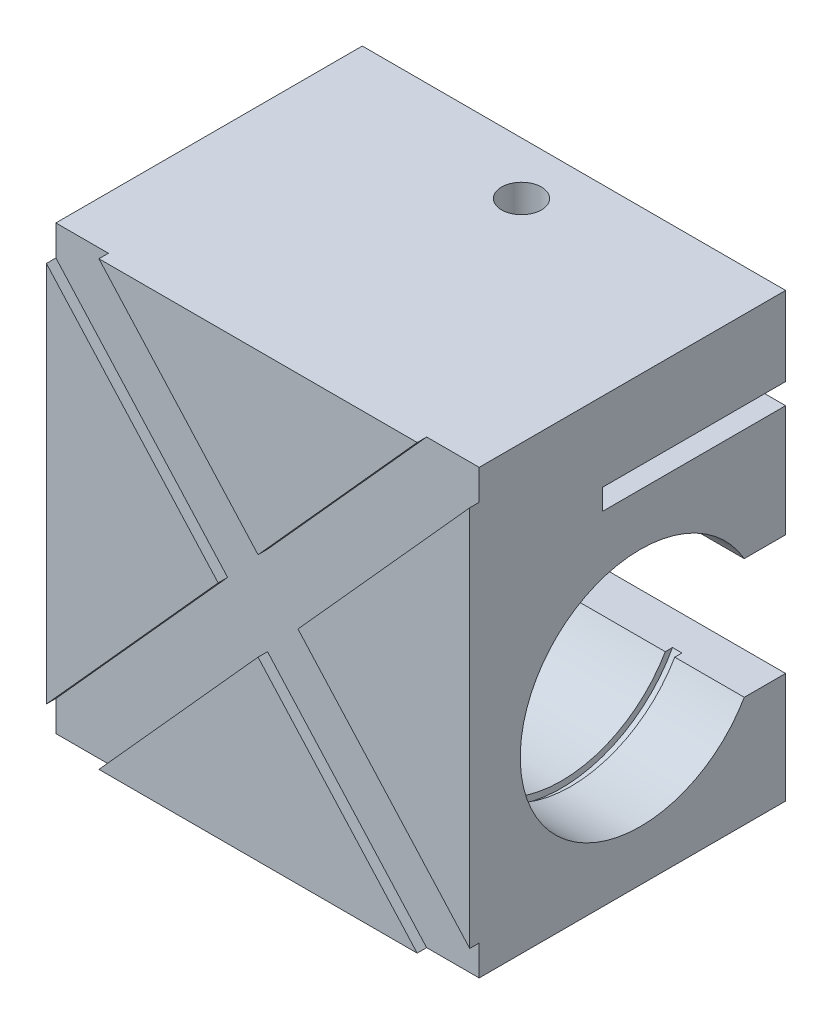
SolidWorks part; units mm, degrees
material "AISI 1020"
ref_plane "Front Plane" through (0, 0, 0) normal (0, 0, 1) x (1, 0, 0)
ref_plane "Top Plane" through (0, 0, 0) normal (0, 1, 0) x (1, 0, 0)
ref_plane "Right Plane" through (0, 0, 0) normal (1, 0, 0) x (0, 0, -1)
sketch "Sketch1" plane through (0, 0, 0) normal (0, 1, 0) x (1, 0, 0)
  line L1 (-33.5, 25) -> (33.5, 25)
  line L2 (-33.5, 25) -> (-33.5, -25)
  line L3 (-33.5, -25) -> (33.5, -25)
  line L4 (33.5, 25) -> (33.5, -25)
  line L5 (-33.5, 25) -> (33.5, -25) construction
  line L6 (-33.5, -25) -> (33.5, 25) construction
  point P0 (0, 0)
  dimension "D1" = 67
  dimension "D2" = 50
extrude "Boss-Extrude1" add sketch "Sketch1" along normal blind 70
sketch "Sketch3" plane through (33.5, 0, 0) normal (1, 0, 0) x (0, 0, -1)
  line L0 (-25, 70) -> (-25, 0) construction
  line L1 (-25, 0) -> (25, 0) construction
  line L2 (25, 57.5) -> (-4, 57.5)
  line L3 (25, 70) -> (25, 0) construction
  line L4 (-4, 57.5) -> (-4, 54.2)
  line L5 (-4, 54.2) -> (25, 54.2)
  line L6 (25, 54.2) -> (25, 57.5)
  line L7 (-25, 70) -> (25, 70) construction
  line L8 (2, 27) -> (25, 27) construction
  line L9 (25, 36.5) -> (25, 17.5)
  line L10 (25, 36.5) -> (18.4545, 36.5)
  line L11 (25, 17.5) -> (18.4545, 17.5)
  arc A0 (18.4545, 36.5) -> (18.4545, 17.5) centre (2, 27) ccw
  point P17 (25, 27)
  dimension "D1" = 38
  dimension "D2" = 27
  dimension "D3" = 27
  dimension "D4" = 3.3
  dimension "D5" = 12.5
  dimension "D6" = 29
  dimension "D7" = 19
extrude "Cut-Extrude1" cut sketch "Sketch3" against normal up to surface (67 mm away) contours L10 A0 L11 L9 | L6 L2 L4 L5 up to face at (-33.5, 35, 0)
ref_plane "Plane1" through (21, 0, 0) normal (1, 0, 0) x (0, 0, -1)
sketch "Sketch4" plane through (21, 0, 0) normal (1, 0, 0) x (0, 0, -1)
  line L0 (2, 0) -> (2, 27) construction
  line L1 (-25, 70) -> (-25, 0) construction
  circle A0 centre (2, 27) radius 20
  dimension "D3" = 40
  dimension "D1" = 27
  dimension "D2" = 27
extrude "Cut-Extrude2" cut sketch "Sketch4" along normal blind 1.5
ref_plane "Plane2" through (-21, 0, 0) normal (1, 0, 0) x (0, 0, -1)
sketch "Sketch5" plane through (-21, 0, 0) normal (1, 0, 0) x (0, 0, -1)
  line L0 (2, 0) -> (2, 27) construction
  line L1 (25, 0) -> (-25, 0) construction
  line L2 (-25, 70) -> (-25, 0) construction
  circle A0 centre (2, 27) radius 20
  dimension "D3" = 40
  dimension "D1" = 27
  dimension "D2" = 27
extrude "Cut-Extrude3" cut sketch "Sketch5" against normal blind 1.5
sketch "Sketch7" plane through (0, 70, 0) normal (0, 1, 0) x (1, 0, 0)
  line L0 (-33.5, 25) -> (-33.5, -25) construction
  line L2 (33.5, 25) -> (-33.5, 25) construction
  circle A0 centre (0, 16.7) radius 3.15
  point P6 (-2.7979, 25)
  dimension "D1" = 6.3
  dimension "D2" = 33.5
  dimension "D3" = 8.3
extrude "Cut-Extrude4" cut sketch "Sketch7" against normal up to surface (12.5 mm away) up to face at (0, 57.5, -10.5)
sketch "Sketch9" plane through (0, 0, 25) normal (0, 0, 1) x (1, 0, 0)
  line L0 (-33.5, 0) -> (-33.5, 4.8)
  line L1 (-33.5, 70) -> (-33.5, 0) construction
  line L2 (-33.5, 0) -> (-25.1862, 0)
  line L3 (-33.5, 0) -> (33.5, 0) construction
  line L4 (0, -1000) -> (0, 49000) construction
  line L5 (33.5, 0) -> (33.5, 4.8)
  line L6 (33.5, 0) -> (25.1862, 0)
  line L7 (-1000, 35) -> (49000, 35) construction
  line L8 (33.5, 70) -> (33.5, 65.2)
  line L9 (33.5, 70) -> (25.1862, 70)
  line L10 (-33.5, 70) -> (-33.5, 65.2)
  line L11 (-33.5, 70) -> (-25.1862, 70)
  line L12 (-33.5, 4.8) -> (-6.3171, 35)
  line L13 (-25.1862, 0) -> (0, 27.9817)
  line L14 (-33.5, 65.2) -> (-6.3171, 35)
  line L15 (-25.1862, 70) -> (0, 42.0183)
  line L16 (0, 42.0183) -> (25.1862, 70)
  line L17 (0, 27.9817) -> (25.1862, 0)
  line L18 (6.3171, 35) -> (33.5, 4.8)
  line L19 (6.3171, 35) -> (33.5, 65.2)
  dimension "D1" = 4.8
  dimension "D2" = 9.6
  dimension "D3" = 35
extrude "Cut-Extrude5" cut sketch "Sketch9" against normal blind 1.5
